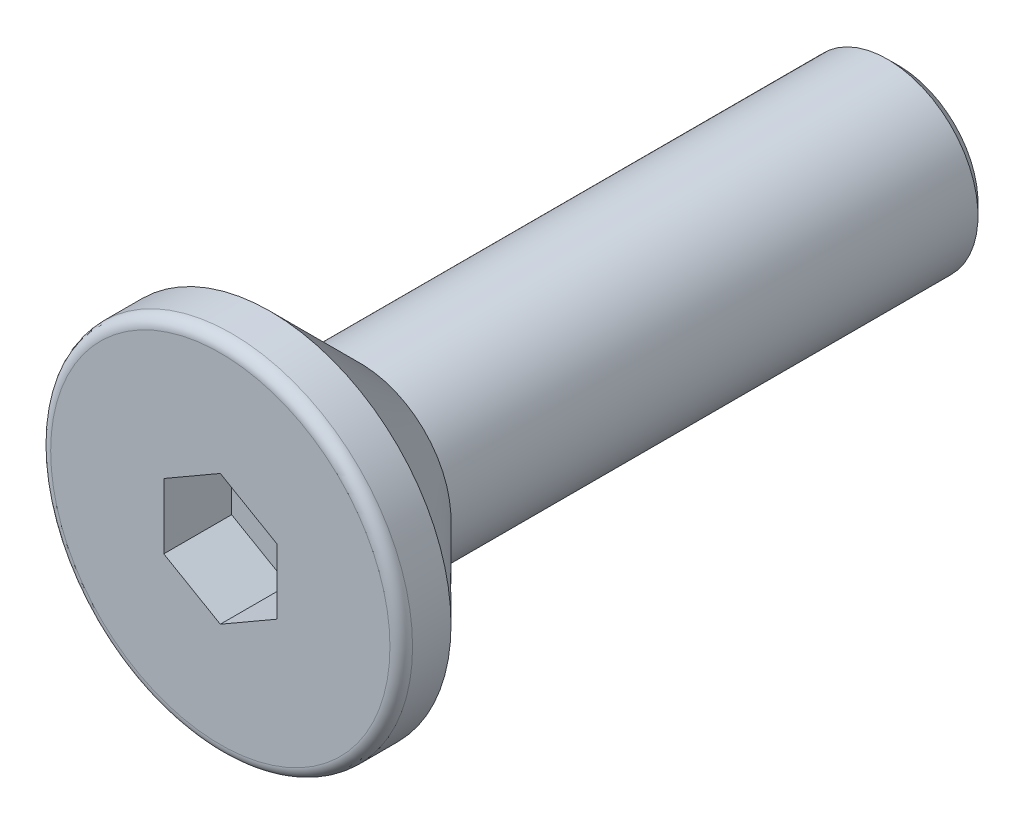
SolidWorks part; units mm, degrees
ref_plane "前视基准面" through (0, 0, 0) normal (0, 0, 1) x (1, 0, 0)
ref_plane "上视基准面" through (0, 0, 0) normal (0, 1, 0) x (1, 0, 0)
ref_plane "右视基准面" through (0, 0, 0) normal (1, 0, 0) x (0, 0, -1)
sketch "草图1" plane through (0, 0, 0) normal (1, 0, 0) x (0, 0, -1)
  line L0 (-15, 0) -> (-15, 8)
  line L1 (-15, 8) -> (-12.8, 8)
  line L2 (-12.8, 8) -> (-8.8, 4)
  line L3 (-8.8, 4) -> (15, 4)
  line L4 (15, 4) -> (15, 0)
  line L5 (15, 0) -> (-15, 0)
  dimension "D1" = 4
  dimension "D2" = 30
  dimension "D3" = 45
  dimension "D4" = 6.2
  dimension "D5" = 8
revolve "旋转1" add sketch "草图1" angle 360 about L5
sketch "草图2" plane through (0, 0, 15) normal (0, 0, 1) x (1, 0, 0)
  line L1 (0, 2.8868) -> (-2.5, 1.4434)
  line L2 (-2.5, 1.4434) -> (-2.5, -1.4434)
  line L3 (-2.5, -1.4434) -> (0, -2.8868)
  line L4 (0, -2.8868) -> (2.5, -1.4434)
  line L5 (2.5, -1.4434) -> (2.5, 1.4434)
  line L6 (2.5, 1.4434) -> (0, 2.8868)
  circle A0 centre (0, 0) radius 2.5 construction
  dimension "D1" = 5
extrude "切除-拉伸1" cut sketch "草图2" against normal blind 3
fillet "圆角1" radius 0.5 1 edges at (-8, 0, 15)
chamfer "倒角1" distance 0.5 angle 45 1 edges at (-4, 0, -15)
